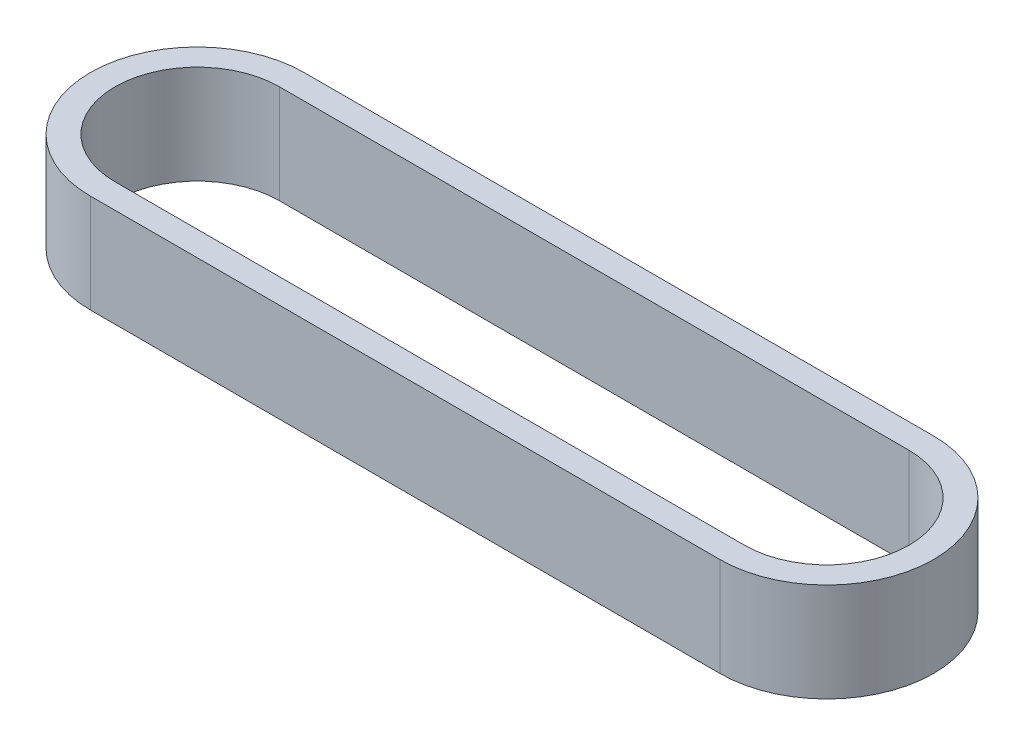
SolidWorks part; units mm, degrees
ref_plane "Front Plane" through (0, 0, 0) normal (0, 0, 1) x (1, 0, 0)
ref_plane "Top Plane" through (0, 0, 0) normal (0, 1, 0) x (1, 0, 0)
ref_plane "Right Plane" through (0, 0, 0) normal (1, 0, 0) x (0, 0, -1)
other "Default"
sketch "Sketch1" plane through (0, 0, 0) normal (0, 1, 0) x (1, 0, 0)
  line L0 (0, 5) -> (38.27, 5)
  line L1 (38.27, -5) -> (0, -5)
  line L2 (0, 6.5) -> (38.27, 6.5)
  line L3 (38.27, -6.5) -> (0, -6.5)
  arc A0 (0, 5) -> (0, -5) centre (0, 0) ccw
  arc A1 (38.27, 5) -> (38.27, -5) centre (38.27, 0) cw
  arc A2 (38.27, 6.5) -> (38.27, -6.5) centre (38.27, 0) cw
  arc A3 (0, 6.5) -> (0, -6.5) centre (0, 0) ccw
  dimension "R1" = 5
  dimension "R2" = 5
  dimension "CenterDistance" = 38.27
  dimension "Thickness" = 1.5
extrude "Boss-Extrude1" add sketch "Sketch1" along normal mid plane 6
